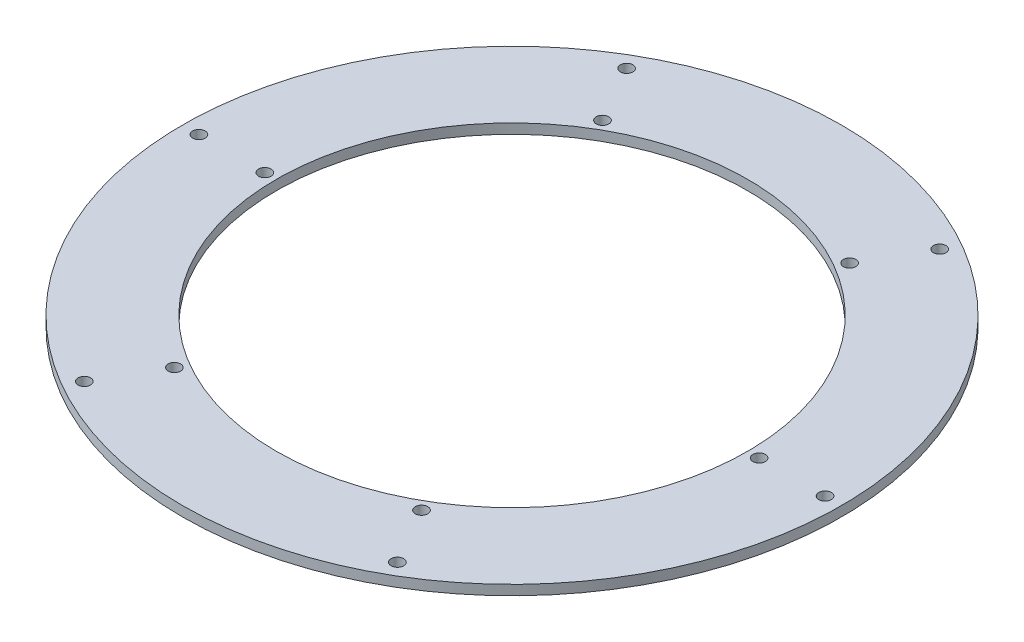
SolidWorks part; units mm, degrees
ref_plane "Ön Düzlem" through (0, 0, 0) normal (0, 0, 1) x (1, 0, 0)
ref_plane "Üst Düzlem" through (0, 0, 0) normal (0, 1, 0) x (1, 0, 0)
ref_plane "Sağ Düzlem" through (0, 0, 0) normal (1, 0, 0) x (0, 0, -1)
sketch "Çizim1" plane through (0, 0, 0) normal (0, 1, 0) x (1, 0, 0)
  circle A0 centre (0, 0) radius 71.5
  circle A1 centre (0, 0) radius 100
  dimension "D1" = 143
extrude "Yükseklik-Ekstrüzyon1" add sketch "Çizim1" along normal blind 3
sketch "Çizim2" plane through (0, 3, 0) normal (0, 1, 0) x (1, 0, 0)
  line L0 (0, 0) -> (-75, 0) construction
  line L1 (-75, 0) -> (-95, 0) construction
  circle A0 centre (-95, 0) radius 1.9
  circle A1 centre (-75, 0) radius 1.9
extrude "Kes-Ekstrüzyon1" cut sketch "Çizim2" against normal through all both and the other way through all
pattern_circular "Dairesel Kaplama1" count 6 over 360 about axis through (0, 0, 0) along (0, 1, 0) of "Kes-Ekstrüzyon1"
